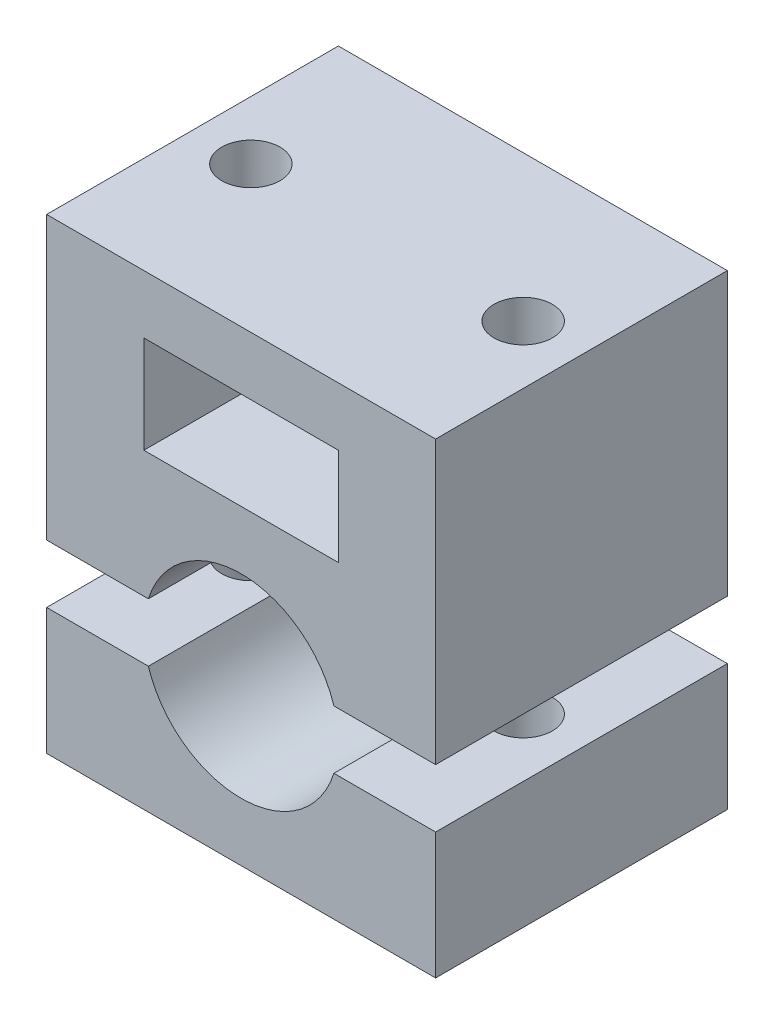
SolidWorks part; units mm, degrees
material "POM 乙缩醛共聚物"
ref_plane "前视基准面" through (0, 0, 0) normal (0, 0, 1) x (1, 0, 0)
ref_plane "上视基准面" through (0, 0, 0) normal (0, 1, 0) x (1, 0, 0)
ref_plane "右视基准面" through (0, 0, 0) normal (1, 0, 0) x (0, 0, -1)
sketch "草图1" plane through (0, 0, 0) normal (0, 0, 1) x (1, 0, 0)
  line L0 (0, 26.6352) -> (0, -24.5239) construction
  line L1 (-32.3037, 0) -> (34.1666, 0) construction
  line L2 (-10, 1.5) -> (-4.7697, 1.5)
  line L3 (-10, 16) -> (10, 16)
  line L4 (-10, 16) -> (-10, 1.5)
  line L5 (-10, -8) -> (10, -8)
  line L6 (10, 16) -> (10, 1.5)
  line L7 (-5, 13) -> (5, 13)
  line L8 (-5, 13) -> (-5, 8)
  line L9 (-5, 8) -> (5, 8)
  line L10 (5, 13) -> (5, 8)
  line L11 (-5, 13) -> (5, 8) construction
  line L12 (-5, 8) -> (5, 13) construction
  line L13 (-10, -1.5) -> (-4.7697, -1.5)
  line L14 (4.7697, 1.5) -> (10, 1.5)
  line L15 (10, -1.5) -> (4.7697, -1.5)
  line L16 (10, -1.5) -> (10, -8)
  line L17 (-10, -1.5) -> (-10, -8)
  arc A0 (4.7697, 1.5) -> (-4.7697, 1.5) centre (0, 0) ccw
  arc A1 (-4.7697, -1.5) -> (4.7697, -1.5) centre (0, 0) ccw
  point P11 (0, 10.5)
  dimension "D2" = 10
  dimension "D1" = 16
  dimension "D3" = 8
  dimension "D4" = 3
  dimension "D5" = 3
  dimension "D6" = 5
  dimension "D7" = 5
  dimension "D8" = 3
extrude "凸台-拉伸1" add sketch "草图1" along normal blind 15
sketch "草图2" plane through (0, -8, 0) normal (0, -1, 0) x (1, 0, 0)
  line L0 (0, 15) -> (0, -9.3433) construction
  line L1 (-10, 15) -> (10, 15) construction
  line L2 (-10, 15) -> (-10, 0) construction
  line L3 (-10, 7.5) -> (10, 7.5) construction
  line L4 (10, 15) -> (10, 0) construction
  circle A0 centre (-7, 7.5) radius 1.5
  circle A1 centre (7, 7.5) radius 1.5
  dimension "D1" = 3
  dimension "D2" = 3
extrude "切除-拉伸1" cut sketch "草图2" against normal through all
